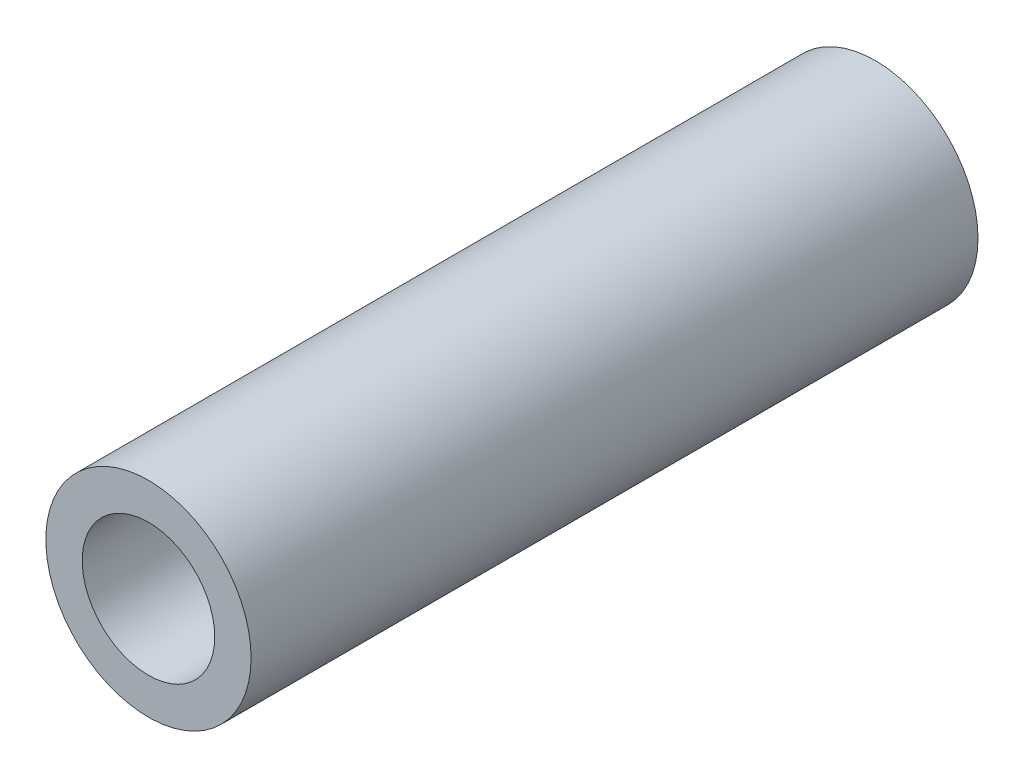
SolidWorks part; units mm, degrees
ref_plane "Front Plane" through (0, 0, 0) normal (0, 0, 1) x (1, 0, 0)
ref_plane "Top Plane" through (0, 0, 0) normal (0, 1, 0) x (1, 0, 0)
ref_plane "Right Plane" through (0, 0, 0) normal (1, 0, 0) x (0, 0, -1)
sketch "Sketch1" plane through (0, 0, 0) normal (0, 0, 1) x (1, 0, 0)
  circle A0 centre (0, 0) radius 2.4
  circle A1 centre (0, 0) radius 1.55
extrude "Boss-Extrude1" add sketch "Sketch1" along normal blind 17
